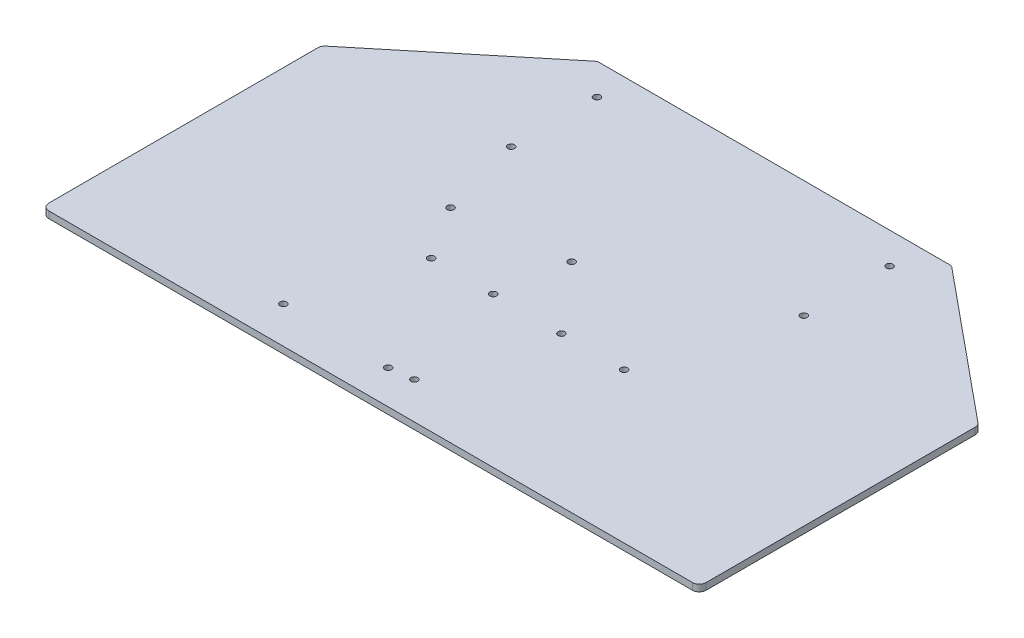
SolidWorks part; units mm, degrees
ref_plane "Front Plane" through (0, 0, 0) normal (0, 0, 1) x (1, 0, 0)
ref_plane "Top Plane" through (0, 0, 0) normal (0, 1, 0) x (1, 0, 0)
ref_plane "Right Plane" through (0, 0, 0) normal (1, 0, 0) x (0, 0, -1)
sketch "Sketch1" plane through (0, 0, 0) normal (0, 1, 0) x (1, 0, 0)
  line L1 (0, 0) -> (297, 0)
  line L2 (0, 0) -> (0, 210)
  line L3 (0, 210) -> (297, 210)
  line L4 (297, 0) -> (297, 210)
  dimension "D1" = 297
  dimension "D2" = 210
extrude "Boss-Extrude1" add sketch "Sketch1" along normal blind 3
sketch "Sketch2" plane through (0, 3, 0) normal (0, 1, 0) x (1, 0, 0)
  line L0 (79.275, 131.849) -> (217.725, 131.849) construction
  line L1 (74.8086, 131.349) -> (228.0925, 131.349) construction
  line L2 (74.8086, 166.599) -> (228.0925, 166.599) construction
  line L3 (217.725, 166.099) -> (79.275, 166.099) construction
  line L4 (0, 210) -> (0, 0) construction
  line L5 (5, 2) -> (292, 2)
  line L6 (2, 5) -> (2, 125)
  line L7 (148.5, 2) -> (148.5, 182) construction
  line L8 (295, 5) -> (295, 125)
  line L9 (297, 0) -> (297, 210) construction
  line L10 (0, 0) -> (297, 0) construction
  line L11 (3.0936, 127.3164) -> (68.7064, 181.3164)
  line L12 (70.6128, 182) -> (226.3872, 182)
  line L13 (293.9064, 127.3164) -> (228.2936, 181.3164)
  line L14 (217.725, 131.849) -> (217.725, 166.099) construction
  line L15 (79.275, 166.099) -> (79.275, 131.849) construction
  circle A0 centre (93.3, 92.8) radius 1.5
  circle A1 centre (141.2, 98.9) radius 1.5
  circle A2 centre (136.2, 68.95) radius 1.5
  circle A3 centre (108.5, 68.95) radius 1.5
  circle A4 centre (93.2, 18.35) radius 1.5
  circle A5 centre (141.2, 17.1) radius 1.5
  circle A6 centre (151.6, 18.4) radius 1.5
  circle A7 centre (166.65, 68.9) radius 1.5
  circle A8 centre (194.6, 68.9) radius 1.5
  circle A9 centre (83.275, 129.849) radius 1.5
  circle A10 centre (213.725, 129.849) radius 1.5
  circle A11 centre (83.275, 168.099) radius 1.5
  circle A12 centre (213.725, 168.099) radius 1.5
  arc A13 (2, 5) -> (5, 2) centre (5, 5) ccw
  arc A14 (292, 2) -> (295, 5) centre (292, 5) ccw
  arc A15 (70.6128, 182) -> (68.7064, 181.3164) centre (70.6128, 179) ccw
  arc A16 (3.0936, 127.3164) -> (2, 125) centre (5, 125) ccw
  arc A17 (293.9064, 127.3164) -> (295, 125) centre (292, 125) cw
  arc A18 (226.3872, 182) -> (228.2936, 181.3164) centre (226.3872, 179) cw
  point P38 (214.5778, 128.5051)
  dimension "D1" = 3
  dimension "D2" = 0.5
  dimension "D7" = 3
  dimension "D3" = 0.5
  dimension "D4" = 2
  dimension "D5" = 2
  dimension "D6" = 2
  dimension "D8" = 180
  dimension "D9" = 120
  dimension "D10" = 4
  dimension "D11" = 4
extrude "Laser Cut Profile" cut sketch "Sketch2" against normal through all flip side to cut
